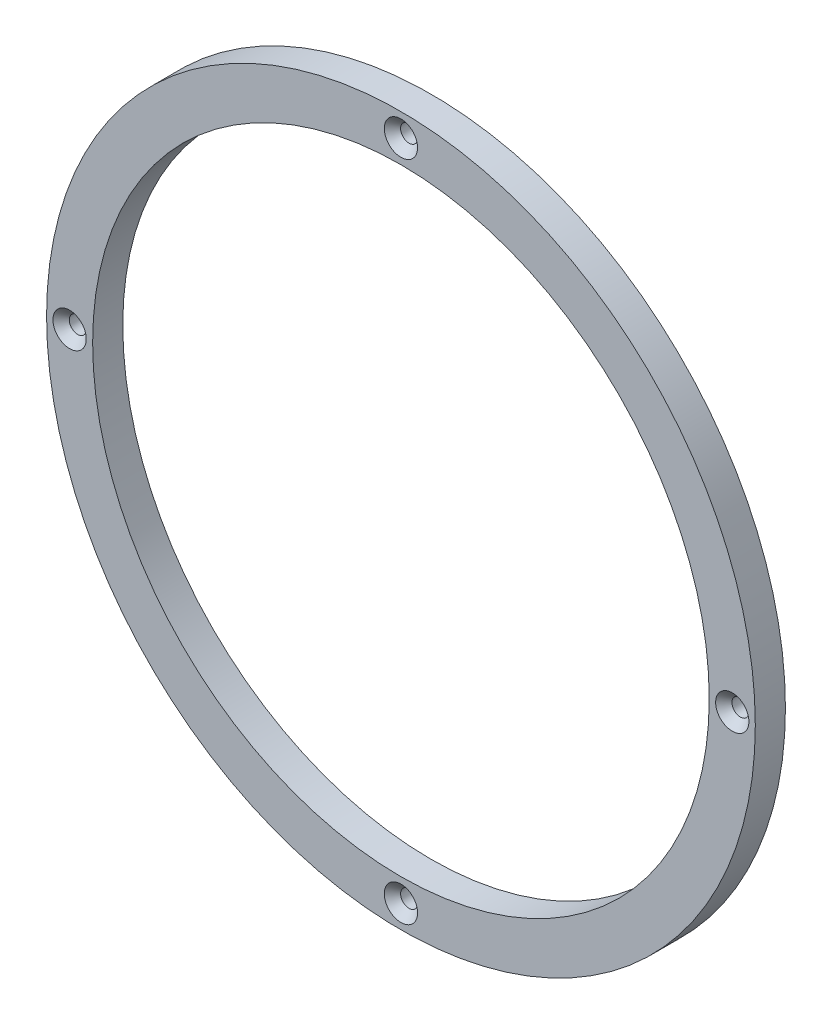
SolidWorks part; units mm, degrees
material "5052-O"
ref_plane "正面" through (0, 0, 0) normal (0, 0, 1) x (1, 0, 0)
ref_plane "平面" through (0, 0, 0) normal (0, 1, 0) x (1, 0, 0)
ref_plane "右側面" through (0, 0, 0) normal (1, 0, 0) x (0, 0, -1)
sketch "ｽｹｯﾁ1" plane through (0, 0, 0) normal (0, 0, 1) x (1, 0, 0)
  circle A0 centre (0, 0) radius 87
  circle A1 centre (0, 0) radius 100
  circle A2 centre (0, 0) radius 93.5
  circle A3 centre (0, 93.5) radius 2.25
  circle A4 centre (93.5, 0) radius 2.25
  circle A5 centre (0, -93.5) radius 2.25
  circle A6 centre (-93.5, 0) radius 2.25
  point P16 (0, 0)
  dimension "D1" = 174
  dimension "D2" = 200
  dimension "D3" = 93.5
  dimension "D4" = 4.5
  dimension "D5" = 4
extrude "ﾎﾞｽ - 押し出し1" add sketch "ｽｹｯﾁ1" along normal blind 8.5 contours A1 A6 A2 A3 A4 A5 | A6 A2 A5 A4 A3 A0
hole_wizard "M4 丸皿ねじ用皿穴1" positions "ｽｹｯﾁ4" profile "ｽｹｯﾁ5" countersink size "M4" standard "JIS" end condition through all
sketch "ｽｹｯﾁ4" plane through (0, 0, 8.5) normal (0, 0, 1) x (1, 0, 0)
  point P0 (-93.5, 0)
  point P3 (0, 93.5)
  point P6 (93.5, 0)
  point P9 (0, -93.5)
sketch "ｽｹｯﾁ5" plane through (-93.5, 0, 8.5) normal (1, 0, 0) x (0, -1, 0)
  line L0 (0, 0) -> (0, 8.5)
  line L1 (0, 8.5) -> (2.4, 8.5)
  line L2 (2.4, 8.5) -> (2.4, 2.3)
  line L3 (2.4, 2.3) -> (4.7, 0)
  line L5 (4.7, 0) -> (0, 0)
  line L6 (-2.4, 2.3) -> (-4.7, 0) construction
  line L11 (0, -6.35) -> (0, 107.95) construction
  dimension "通し穴の直径" = 4.8
  dimension "通し穴の深さ" = 8.5
  dimension "表面の皿穴の直径" = 9.4
  dimension "表面の皿穴の角度" = 90
